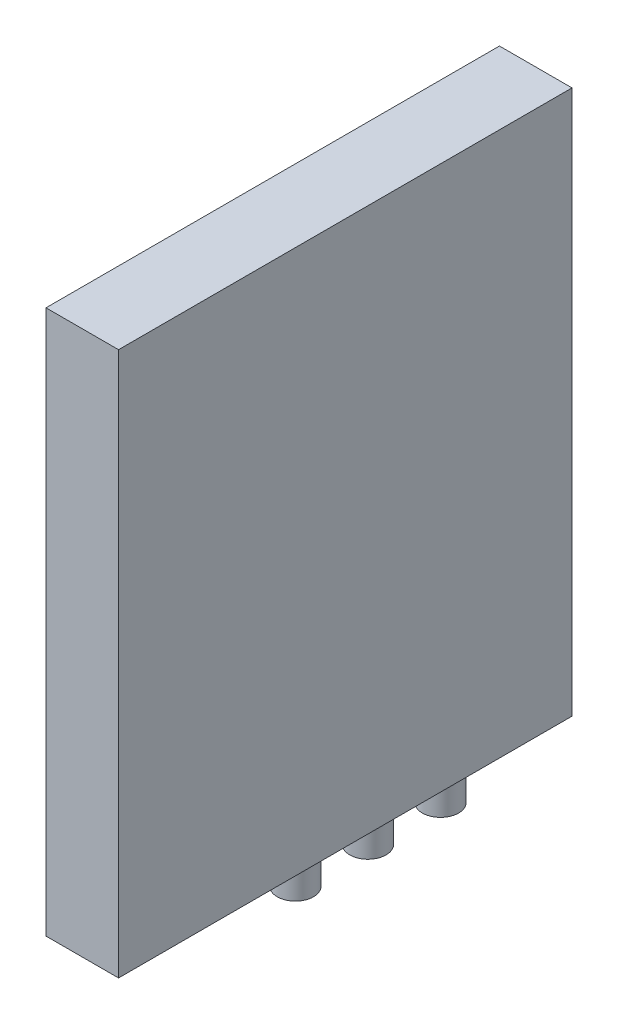
SolidWorks part; units mm, degrees
ref_plane "Front Plane" through (0, 0, 0) normal (0, 0, 1) x (1, 0, 0)
ref_plane "Top Plane" through (0, 0, 0) normal (0, 1, 0) x (1, 0, 0)
ref_plane "Right Plane" through (0, 0, 0) normal (1, 0, 0) x (0, 0, -1)
sketch "Sketch2" plane through (0, 0, 0) normal (0, 1, 0) x (1, 0, 0)
  line L0 (-37.2311, 32.3785) -> (37.7689, -6.6215) construction
  line L1 (-57.2311, 37.3785) -> (42.7689, 37.3785) construction
  line L2 (-57.2311, 37.3785) -> (-57.2311, -24.6215) construction
  line L3 (-57.2311, -24.6215) -> (42.7689, -24.6215) construction
  line L4 (42.7689, 37.3785) -> (42.7689, -24.6215) construction
  line L5 (-37.2311, -6.6215) -> (37.7689, 32.3785) construction
  line L7 (-58.2311, 38.3785) -> (43.7689, 38.3785) construction
  line L8 (-58.2311, 38.3785) -> (-58.2311, -25.6215) construction
  line L9 (-58.2311, -25.6215) -> (43.7689, -25.6215) construction
  line L10 (43.7689, 38.3785) -> (43.7689, -25.6215) construction
  line L11 (-61.2311, 41.3785) -> (46.7689, 41.3785)
  line L12 (-61.2311, 41.3785) -> (-61.2311, -28.6215)
  line L13 (-61.2311, -28.6215) -> (46.7689, -28.6215)
  line L14 (46.7689, 41.3785) -> (46.7689, -28.6215)
  line L15 (-23.7311, 31.3785) -> (-15.7311, 31.3785)
  line L16 (-23.7311, 31.3785) -> (-23.7311, -18.6215)
  line L17 (-23.7311, -18.6215) -> (-15.7311, -18.6215)
  line L18 (-15.7311, 31.3785) -> (-15.7311, -18.6215)
  circle A0 centre (20.2689, 4.8785) radius 2.25
  circle A1 centre (10.2689, 4.8785) radius 2.25
  circle A2 centre (0.2689, 4.8785) radius 2.25
  circle A3 centre (10.2689, 12.8785) radius 2.25
  circle A4 centre (0.2689, 12.8785) radius 2.25
  circle A5 centre (10.2689, 20.8785) radius 2.25
  circle A6 centre (0.2689, 20.8785) radius 2.25
  circle A7 centre (20.2689, 12.8785) radius 2.25
  circle A8 centre (20.2689, 20.8785) radius 2.25
  circle A9 centre (-9.7311, 4.8785) radius 2.25
  circle A10 centre (-9.7311, 12.8785) radius 2.25
  circle A11 centre (-9.7311, 20.8785) radius 2.25
  circle A12 centre (-19.7311, 4.8785) radius 2.25
  circle A13 centre (-19.7311, 12.8785) radius 2.25
  circle A14 centre (-19.7311, 20.8785) radius 2.25
  point P4 (-37.2311, 32.3785)
  point P5 (37.7689, 32.3785)
  point P6 (37.7689, -6.6215)
  point P7 (-37.2311, -6.6215)
  point P9 (20.2689, 4.8785)
  point P38 (-37.2311, 32.3785)
  point P41 (0.2689, 12.8785)
  point P59 (-19.7311, -18.6215)
  dimension "D11" = 4.5
  dimension "D12" = 5
  dimension "D1" = 62
  dimension "D2" = 100
  dimension "D3" = 5
  dimension "D4" = 20
  dimension "D5" = 5
  dimension "D6" = 5
  dimension "D7" = 18
  dimension "D8" = 20
  dimension "D9" = 18
  dimension "D10" = 5
  dimension "D13" = 3
  dimension "D14" = 1
  dimension "D15" = 3
  dimension "D16" = 1
  dimension "D17" = 3
  dimension "D18" = 1
  dimension "D19" = 3
  dimension "D20" = 1
  dimension "D21" = 3
  dimension "D22" = 8
  dimension "D23" = 10
  dimension "D24" = 10
extrude "Boss-Extrude1" add sketch "Sketch2" along normal blind 60 contours L18 L15 L16 L17 A14 A13 A12 | A14 | A13 | A12
sketch "Sketch3" plane through (0, 0, 0) normal (0, -1, 0) x (1, 0, 0)
  circle A0 centre (-19.7311, -4.8785) radius 2
  circle A1 centre (-19.7311, -4.8785) radius 2.25 construction
  circle A2 centre (-19.7311, -12.8785) radius 2
  circle A3 centre (-19.7311, -20.8785) radius 2
  dimension "D1" = 0.25
  dimension "D2" = 3
extrude "Boss-Extrude2" add sketch "Sketch3" along normal blind 5
